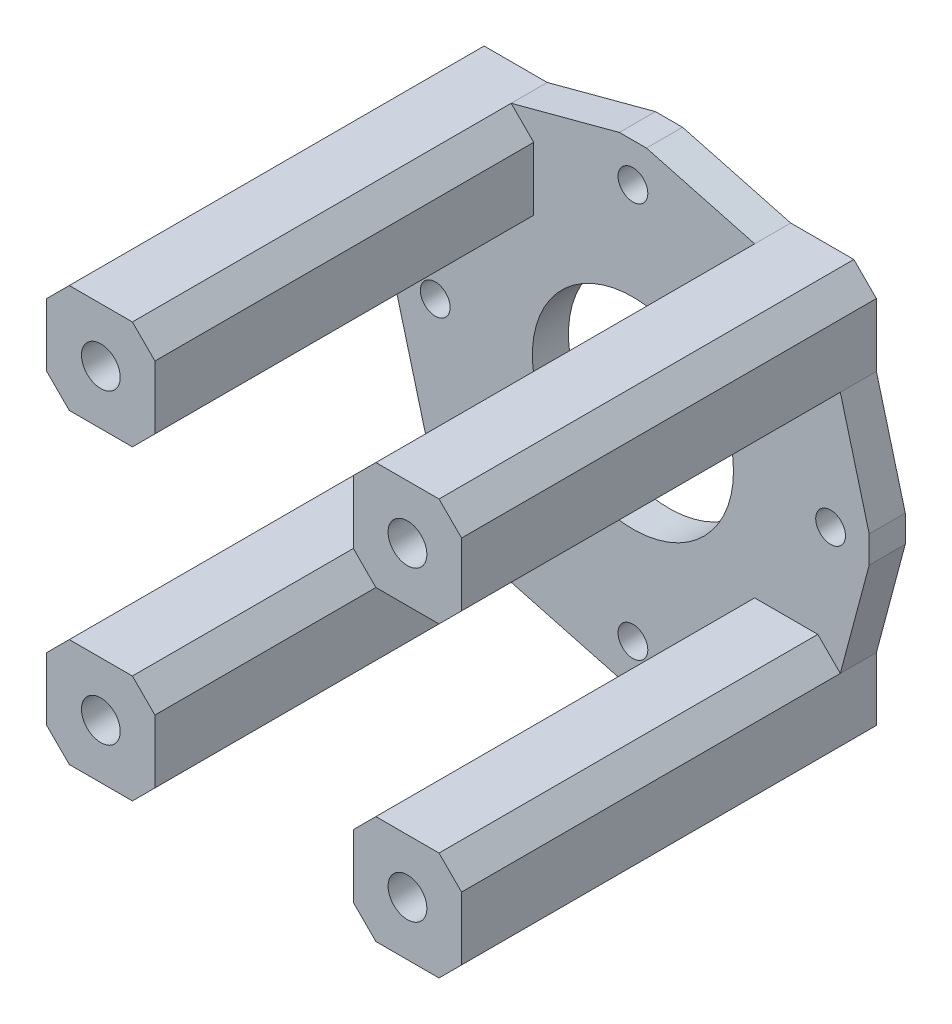
SolidWorks part; units mm, degrees
ref_plane "Front Plane" through (0, 0, 0) normal (0, 0, 1) x (1, 0, 0)
ref_plane "Top Plane" through (0, 0, 0) normal (0, 1, 0) x (1, 0, 0)
ref_plane "Right Plane" through (0, 0, 0) normal (1, 0, 0) x (0, 0, -1)
sketch "Sketch1" plane through (0, 0, 0) normal (0, 0, 1) x (1, 0, 0)
  line L0 (-21.9203, 0) -> (21.9203, 0) construction
  line L1 (17, -17) -> (-17, -17) construction
  line L2 (17, -17) -> (17, 17) construction
  line L3 (17, 17) -> (-17, 17) construction
  line L4 (-17, -17) -> (-17, 17) construction
  line L5 (17, -17) -> (-17, 17) construction
  line L6 (17, 17) -> (-17, -17) construction
  line L7 (25, -25) -> (-25, -25)
  line L8 (25, -25) -> (25, 25)
  line L9 (25, 25) -> (-25, 25)
  line L10 (-25, -25) -> (-25, 25)
  line L11 (25, -25) -> (-25, 25) construction
  line L12 (25, 25) -> (-25, -25) construction
  line L13 (0, 21.9203) -> (0, -21.9203) construction
  circle A0 centre (0, 0) radius 11.15
  circle A1 centre (-17, 17) radius 2.15
  circle A2 centre (17, 17) radius 2.15
  circle A3 centre (17, -17) radius 2.15
  circle A4 centre (-17, -17) radius 2.15
  circle A5 centre (-21.9203, 0) radius 1.65
  circle A6 centre (0, 21.9203) radius 1.65
  circle A7 centre (21.9203, 0) radius 1.65
  circle A8 centre (0, -21.9203) radius 1.65
  point P0 (0, 0)
  point P6 (0, 0)
  point P17 (0, 0)
  point P18 (0, 0)
  dimension "D1" = 22.3
  dimension "D4" = 3.3
  dimension "D5" = 4.3
  dimension "D2" = 31
  dimension "D3" = 50
  dimension "D6" = 34
extrude "Boss-Extrude1" add sketch "Sketch1" against normal blind 4
sketch "Sketch2" plane through (0, 0, 0) normal (0, 0, 1) x (1, 0, 0)
  line L1 (-11, 11) -> (-23, 11)
  line L2 (-11, 11) -> (-11, 23)
  line L3 (-11, 23) -> (-23, 23)
  line L4 (-23, 11) -> (-23, 23)
  line L5 (-11, 11) -> (-23, 23) construction
  line L6 (-11, 23) -> (-23, 11) construction
  line L7 (11, 11) -> (23, 11)
  line L8 (11, 11) -> (11, 23)
  line L9 (11, 23) -> (23, 23)
  line L10 (23, 11) -> (23, 23)
  line L11 (11, 11) -> (23, 23) construction
  line L12 (11, 23) -> (23, 11) construction
  line L13 (11, -11) -> (23, -11)
  line L14 (11, -11) -> (11, -23)
  line L15 (11, -23) -> (23, -23)
  line L16 (23, -11) -> (23, -23)
  line L17 (11, -11) -> (23, -23) construction
  line L18 (11, -23) -> (23, -11) construction
  line L19 (-11, -11) -> (-23, -11)
  line L20 (-11, -11) -> (-11, -23)
  line L21 (-11, -23) -> (-23, -23)
  line L22 (-23, -11) -> (-23, -23)
  line L23 (-11, -11) -> (-23, -23) construction
  line L24 (-11, -23) -> (-23, -11) construction
  line L25 (23, -23) -> (-23, -23) construction
  line L26 (23, -23) -> (23, 23) construction
  line L27 (23, 23) -> (-23, 23) construction
  line L28 (-23, -23) -> (-23, 23) construction
  line L29 (23, -23) -> (-23, 23) construction
  line L30 (23, 23) -> (-23, -23) construction
  circle A0 centre (-17, 17) radius 2.15
  circle A1 centre (17, 17) radius 2.15
  circle A2 centre (17, -17) radius 2.15
  circle A3 centre (-17, -17) radius 2.15
  circle A4 centre (-17, 17) radius 2.15 construction
  circle A5 centre (17, 17) radius 2.15 construction
  circle A6 centre (17, -17) radius 2.15 construction
  circle A7 centre (-17, -17) radius 2.15 construction
  point P0 (-17, 17)
  point P7 (17, 17)
  point P14 (17, -17)
  point P21 (-17, -17)
  point P49 (0, 0)
  dimension "D1" = 46
extrude "Boss-Extrude2" add sketch "Sketch2" along normal blind 42
chamfer "Chamfer1" distance 2.5 angle 45 16 edges at (-11, -11, 21) (11, -23, 21) (11, -11, 21) (23, 11, 21) (11, 11, 21) (-11, 23, 21) (-11, 11, 21) (-23, 11, 21) (-11, -23, 21) (-23, -23, 21) (-23, -11, 21) (23, -23, 21) (23, -11, 21) (11, 23, 21) (23, 23, 21) (-23, 23, 21)
sketch "Sketch3" plane through (0, 0, 42) normal (0, 0, 1) x (1, 0, 0)
  circle A0 centre (-17, 17) radius 4.5
  circle A1 centre (17, 17) radius 4.5
  circle A2 centre (17, -17) radius 4.5
  circle A3 centre (-17, -17) radius 4.5
  dimension "D1" = 9
extrude "Cut-Extrude1" cut sketch "Sketch3" against normal through all from offset 8 offset against normal yes
sketch "Sketch5" plane through (0, 0, 0) normal (0, 0, 1) x (1, 0, 0)
  line L0 (-23, 20.5) -> (-20.5, 23)
  line L1 (-20.5, 23) -> (-13.5, 23)
  line L3 (-13.5, 23) -> (-6, 25)
  line L4 (25, 25) -> (-25, 25) construction
  line L5 (20.5, 23) -> (23, 20.5)
  line L6 (23, 20.5) -> (23, 13.5)
  line L7 (25, -25) -> (25, 25) construction
  line L8 (25, 6) -> (25, -6)
  line L9 (23, 13.5) -> (25, 6)
  line L10 (23, -20.5) -> (20.5, -23)
  line L11 (20.5, -23) -> (13.5, -23)
  line L12 (13.5, -23) -> (6, -25)
  line L13 (-25, -25) -> (25, -25) construction
  line L14 (6, -25) -> (-6, -25)
  line L15 (-6, -25) -> (-13.5, -23)
  line L16 (-13.5, -23) -> (-20.5, -23)
  line L17 (-20.5, -23) -> (-23, -20.5)
  line L18 (-23, -20.5) -> (-23, -13.5)
  line L19 (-23, -13.5) -> (-25, -6)
  line L20 (-25, 25) -> (-25, -25) construction
  line L21 (-25, -6) -> (-25, 6)
  line L22 (-25, 6) -> (-23, 13.5)
  line L23 (-23, 13.5) -> (-23, 20.5)
  line L24 (-6, 25) -> (6, 25)
  line L25 (6, 25) -> (13.5, 23)
  line L26 (13.5, 23) -> (20.5, 23)
  line L27 (25, -6) -> (23, -13.5)
  line L28 (23, -13.5) -> (23, -20.5)
  line L29 (0, 25) -> (0, -25) construction
  line L30 (-25, 0) -> (25, 0) construction
  line L31 (28, -28) -> (-28, -28)
  line L32 (28, -28) -> (28, 28)
  line L33 (28, 28) -> (-28, 28)
  line L34 (-28, -28) -> (-28, 28)
  line L35 (28, -28) -> (-28, 28) construction
  line L36 (28, 28) -> (-28, -28) construction
  point P7 (0, 0)
  point P51 (0, 0)
  dimension "D1" = 12
  dimension "D2" = 3
extrude "Cut-Extrude2" cut sketch "Sketch5" against normal through all
sketch "Sketch6" plane through (0, 0, 0) normal (0, 0, 1) x (1, 0, 0)
  line L0 (-6, 25) -> (-1.5, 26.2)
  line L1 (-1.5, 26.2) -> (1.5, 26.2)
  line L2 (1.5, 26.2) -> (6, 25)
  line L3 (0, 26.2) -> (0, 25) construction
  line L4 (6, 25) -> (-6, 25) construction
  line L5 (-6, 25) -> (6, 25)
  line L6 (13.5, 23) -> (6, 25) construction
  dimension "D1" = 1.2
extrude "Boss-Extrude3" add sketch "Sketch6" against normal up to surface (4 mm away) up to face at (-12.5, -17, -4)
pattern_circular "CirPattern1" count 4 over 360 about axis through (0, 0, 0) along (0, 0, 1) of "Boss-Extrude3"
